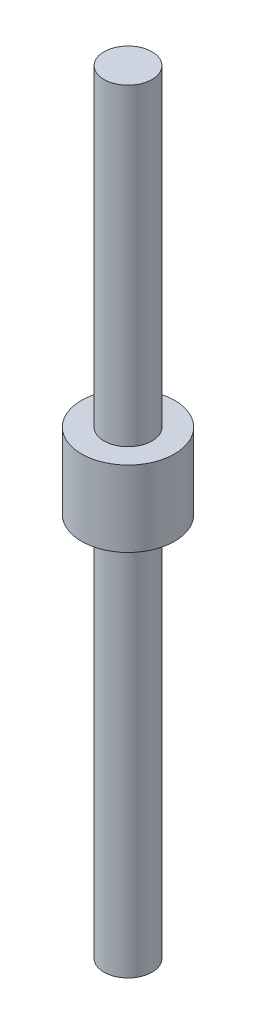
SolidWorks part; units mm, degrees
ref_plane "Front Plane" through (0, 0, 0) normal (0, 0, 1) x (1, 0, 0)
ref_plane "Top Plane" through (0, 0, 0) normal (0, 1, 0) x (1, 0, 0)
ref_plane "Right Plane" through (0, 0, 0) normal (1, 0, 0) x (0, 0, -1)
sketch "Sketch1" plane through (0, 0, 0) normal (0, 0, 1) x (1, 0, 0)
  line L0 (0, 0) -> (0, 49.1107) construction
  line L1 (0, 0) -> (0, 102.1874)
  line L2 (0, 0) -> (3.175, 0)
  line L4 (3.175, 0) -> (3.175, 50.8)
  line L6 (3.175, 50.8) -> (6.1452, 50.8)
  line L7 (3.175, 60.8085) -> (6.1452, 60.8085)
  line L8 (6.1452, 50.8) -> (6.1452, 60.8085)
  line L9 (3.175, 60.8085) -> (3.175, 102.1874)
  line L10 (3.175, 102.1874) -> (0, 102.1874)
  point P3 (0, 49.1107)
  point P12 (0, 42.5724)
  dimension "D1" = 6.35
  dimension "D2" = 50.8
revolve "Revolve1" add sketch "Sketch1" angle 360 about L0
